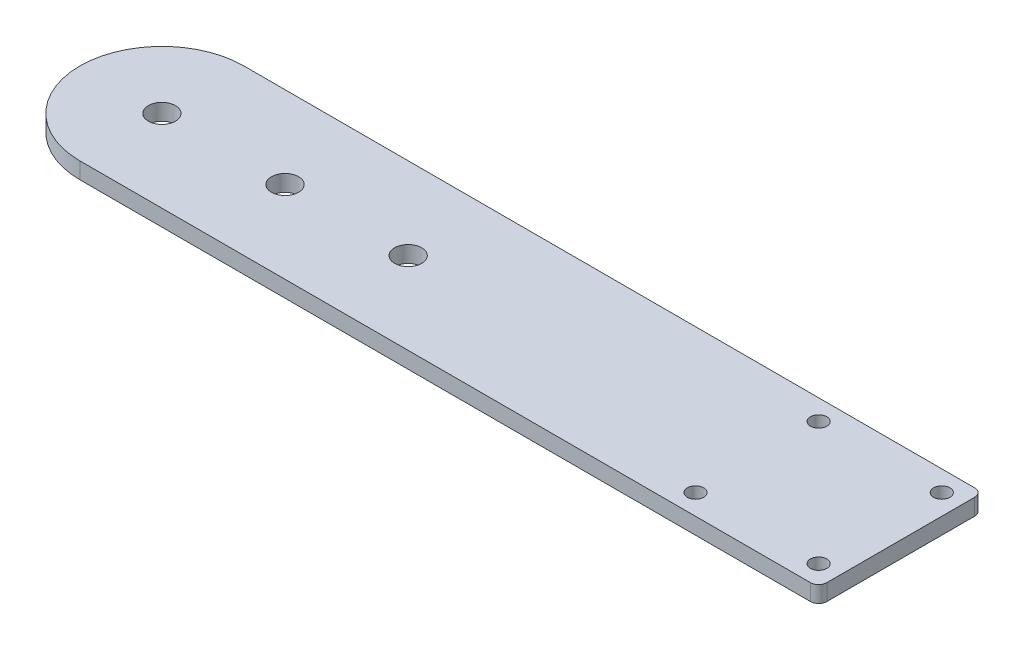
SolidWorks part; units mm, degrees
material "1060 Сплав"
ref_plane "Спереди" through (0, 0, 0) normal (0, 0, 1) x (1, 0, 0)
ref_plane "Сверху" through (0, 0, 0) normal (0, 1, 0) x (1, 0, 0)
ref_plane "Справа" through (0, 0, 0) normal (1, 0, 0) x (0, 0, -1)
sketch "Эскиз1" plane through (0, 0, 0) normal (0, 1, 0) x (1, 0, 0)
  line L0 (0, 10) -> (90, 10)
  line L1 (0, -10) -> (90, -10)
  line L2 (90, 10) -> (90, -10)
  line L3 (72.5, 7.5) -> (87.5, 7.5) construction
  line L4 (87.5, 7.5) -> (87.5, -7.5) construction
  line L5 (87.5, -7.5) -> (72.5, -7.5) construction
  line L6 (87.5, 8.5) -> (72.5, 8.5) construction
  line L7 (88.5, 7.5) -> (88.5, -8.5) construction
  line L8 (88.5, -8.5) -> (72.5, -8.5) construction
  line L9 (72.5, -8.5) -> (72.5, 8.5) construction
  arc A0 (0, 10) -> (0, -10) centre (0, 0) ccw
  circle A1 centre (30, 0) radius 1.65
  circle A2 centre (0, 0) radius 1.65
  circle A3 centre (15, 0) radius 1.65
  circle A6 centre (87.5, 7.5) radius 1
  circle A7 centre (72.5, 7.5) radius 1
  circle A8 centre (87.5, -7.5) radius 1
  circle A9 centre (72.5, -7.5) radius 1
  point P3 (15, 0)
  point P28 (80, 0)
  point P31 (65, 0)
  dimension "D1" = 65
  dimension "D2" = 3.3
  dimension "D3" = 20
  dimension "D4" = 80
  dimension "D5" = 7.5
  dimension "D7" = 15
  dimension "D6" = 7.5
  dimension "D8" = 15
  dimension "D9" = 2.5
  dimension "D12" = 2
  dimension "D11" = 30
extrude "Бобышка-Вытянуть1" add sketch "Эскиз1" along normal blind 2
fillet "Скругление1" radius 1 2 edges at (90, 1, 10) (90, 1, -10)
